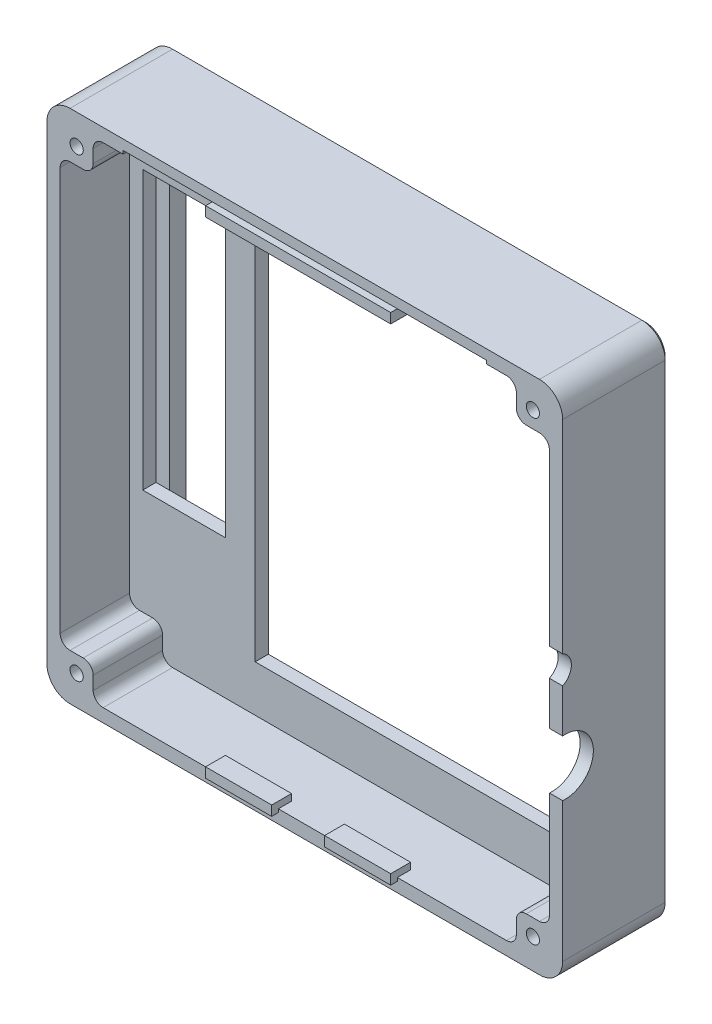
SolidWorks part; units mm, degrees
ref_plane "前视基准面" through (0, 0, 0) normal (0, 0, 1) x (1, 0, 0)
ref_plane "上视基准面" through (0, 0, 0) normal (0, 1, 0) x (1, 0, 0)
ref_plane "右视基准面" through (0, 0, 0) normal (1, 0, 0) x (0, 0, -1)
other "Configuration Table"
sketch "草图1" plane through (0, 0, 0) normal (0, 0, 1) x (1, 0, 0)
  line L1 (-39, -39) -> (39, -39)
  line L2 (-39, -39) -> (-39, 39)
  line L3 (-39, 39) -> (39, 39)
  line L4 (39, -39) -> (39, 39)
  line L5 (-39, -39) -> (39, 39) construction
  line L6 (-39, 39) -> (39, -39) construction
  point P0 (0, 0)
  dimension "D1" = 78
extrude "凸台-拉伸1" add sketch "草图1" along normal blind 5.5
sketch "草图2" plane through (0, 0, 5.5) normal (0, 0, 1) x (1, 0, 0)
  line L1 (-39, -39) -> (39, -39)
  line L2 (-39, -39) -> (-39, 39)
  line L3 (-39, 39) -> (39, 39)
  line L4 (39, -39) -> (39, 39)
  line L5 (-39, -39) -> (39, 39) construction
  line L6 (-39, 39) -> (39, -39) construction
  line L7 (37, 37) -> (-37, 37)
  line L8 (37, 37) -> (37, -37)
  line L9 (37, -37) -> (-37, -37)
  line L10 (-37, 37) -> (-37, -37)
  line L11 (37, 37) -> (-37, -37) construction
  line L12 (37, -37) -> (-37, 37) construction
  line L13 (-37, 37) -> (-32, 37)
  line L14 (-37, 37) -> (-37, 32)
  line L15 (-37, 32) -> (-32, 32)
  line L16 (-32, 37) -> (-32, 32)
  line L17 (37, 37) -> (32, 37)
  line L18 (37, 37) -> (37, 32)
  line L19 (37, 32) -> (32, 32)
  line L20 (32, 37) -> (32, 32)
  line L21 (-37, -37) -> (-32, -37)
  line L22 (-37, -37) -> (-37, -32)
  line L23 (-37, -32) -> (-32, -32)
  line L24 (-32, -37) -> (-32, -32)
  line L25 (37, -37) -> (32, -37)
  line L26 (37, -37) -> (37, -32)
  line L27 (37, -32) -> (32, -32)
  line L28 (32, -37) -> (32, -32)
  point P0 (0, 0)
  point P7 (0, 0)
  line M22 (39, -39) -> (39, 39)
  line M23 (39, 39) -> (-39, 39)
  line M24 (-39, 39) -> (-39, -39)
  line M25 (-39, -39) -> (39, -39)
  dimension "D1" = 2
  dimension "D2" = 5
extrude "凸台-拉伸2" add sketch "草图2" along normal blind 10.5 contours L10 L7 L8 L9 M25 M22 M23 M24 | L16 L7 L10 L15 | L7 L20 L19 L8 | L28 L9 L8 L27 | L9 L24 L23 L10
fillet "圆角1" radius 1.5 12 edges at (37, 32, 10.75) (32, 32, 10.75) (32, 37, 10.75) (37, -32, 10.75) (32, -32, 10.75) (32, -37, 10.75) (-32, -37, 10.75) (-32, -32, 10.75) (-37, -32, 10.75) (-37, 32, 10.75) (-32, 37, 10.75) (-32, 32, 10.75)
fillet "圆角2" radius 3.5 4 edges at (-39, 39, 8) (39, 39, 8) (39, -39, 8) (-39, -39, 8)
sketch "草图3" plane through (0, 0, 0) normal (0, 0, -1) x (-1, 0, 0)
  line L8 (37.5, -35.5) -> (37.5, 35.5)
  line L9 (-35.5, -37.5) -> (35.5, -37.5)
  line L10 (-37.5, 35.5) -> (-37.5, -35.5)
  line L11 (35.5, 37.5) -> (-35.5, 37.5)
  line L12 (37.5, -35.5) -> (37.5, 35.5)
  line L13 (-35.5, -37.5) -> (35.5, -37.5)
  line L14 (-37.5, 35.5) -> (-37.5, -35.5)
  line L15 (35.5, 37.5) -> (-35.5, 37.5)
  arc A8 (37.5, 35.5) -> (35.5, 37.5) centre (35.5, 35.5) ccw
  arc A9 (35.5, -37.5) -> (37.5, -35.5) centre (35.5, -35.5) ccw
  arc A10 (-37.5, -35.5) -> (-35.5, -37.5) centre (-35.5, -35.5) ccw
  arc A11 (-35.5, 37.5) -> (-37.5, 35.5) centre (-35.5, 35.5) ccw
  arc A12 (37.5, 35.5) -> (35.5, 37.5) centre (35.5, 35.5) ccw
  arc A13 (35.5, -37.5) -> (37.5, -35.5) centre (35.5, -35.5) ccw
  arc A14 (-37.5, -35.5) -> (-35.5, -37.5) centre (-35.5, -35.5) ccw
  arc A15 (-35.5, 37.5) -> (-37.5, 35.5) centre (-35.5, 35.5) ccw
  dimension "D1" = 1.5
extrude "切除-拉伸1" cut sketch "草图3" against normal blind 1
sketch "草图4" plane through (0, 0, 1) normal (0, 0, -1) x (-1, 0, 0)
  line L0 (35.5, 37.5) -> (-35.5, 37.5) construction
  line L1 (-32.95, 37.5) -> (32.95, 37.5)
  line L2 (-32.95, 37.5) -> (-32.95, -33)
  line L3 (-32.95, -33) -> (32.95, -33)
  line L4 (32.95, 37.5) -> (32.95, -33)
  line L6 (0, 0) -> (0, 26.6317) construction
  line L7 (-32.95, 36.85) -> (32.95, 36.85)
  line L8 (27.5, 36.85) -> (27.5, 37.5)
  line L9 (-27.5, 36.85) -> (-27.5, 37.5)
  line M10 (35.5, 37.5) -> (-35.5, 37.5)
  dimension "D1" = 70.5
  dimension "D2" = 65.9
  dimension "D3" = 0.65
  dimension "D4" = 55
extrude "切除-拉伸2" cut sketch "草图4" against normal blind 2.5 contours L3 L6 L7 L2 | L6 L3 L4 L7 | L7 L6 L9 M10 | L6 L7 L8 L1
sketch "草图5" plane through (0, 0, 1) normal (0, 0, -1) x (-1, 0, 0)
  line L0 (-35.5, 39) -> (35.5, 39) construction
  line L1 (-34.5, -34.5) -> (34.5, -34.5) construction
  line L2 (-34.5, -34.5) -> (-34.5, 34.5) construction
  line L3 (-34.5, 34.5) -> (34.5, 34.5) construction
  line L4 (34.5, -34.5) -> (34.5, 34.5) construction
  line L5 (-34.5, -34.5) -> (34.5, 34.5) construction
  line L6 (-34.5, 34.5) -> (34.5, -34.5) construction
  circle A0 centre (-34.5, 34.5) radius 1
  circle A1 centre (34.5, 34.5) radius 1
  circle A2 centre (34.5, -34.5) radius 1
  circle A3 centre (-34.5, -34.5) radius 1
  point P0 (0, 0)
  dimension "D2" = 2
  dimension "D1" = 4.5
extrude "切除-拉伸3" cut sketch "草图5" against normal through all
chamfer "倒角1" distance 0.5 angle 45 8 edges at (-39, 0, 0) (-37.9749, -37.9749, 0) (-37.9749, 37.9749, 0) (0, -39, 0) (0, 39, 0) (37.9749, -37.9749, 0) (37.9749, 37.9749, 0) (39, 0, 0)
sketch "草图6" plane through (0, 0, 3.5) normal (0, 0, -1) x (-1, 0, 0)
  line L1 (-27.5, 37.5) -> (27.5, 37.5)
  line L2 (-27.5, 37.5) -> (-27.5, 35.5)
  line L3 (-27.5, 35.5) -> (27.5, 35.5)
  line L4 (27.5, 37.5) -> (27.5, 35.5)
  line L5 (-36, 28) -> (18, 28)
  line L6 (-36, 28) -> (-36, -30)
  line L7 (-36, -30) -> (18, -30)
  line L8 (18, 28) -> (18, -30)
  line L9 (22.5, 26) -> (35, 26)
  line L10 (22.5, 26) -> (22.5, -16)
  line L11 (22.5, -16) -> (35, -16)
  line L12 (35, 26) -> (35, -16)
  dimension "D1" = 2
  dimension "D2" = 54
  dimension "D3" = 30
  dimension "D4" = 58
  dimension "D5" = 36
  dimension "D6" = 22.5
  dimension "D7" = 12.5
  dimension "D8" = 42
  dimension "D9" = 16
extrude "切除-拉伸4" cut sketch "草图6" against normal through all
sketch "草图7" plane through (0, 0, 16) normal (0, 0, 1) x (1, 0, 0)
  line L0 (-15.0283, 0) -> (15.498, 0) construction
  line L17 (0, -8.9343) -> (0, 15.7561) construction
  line L20 (35.5, -37.5) -> (-35.5, -37.5) construction
  line L21 (14, -37.5) -> (4, -37.5)
  line L22 (14, -37.5) -> (14, -36)
  line L23 (14, -36) -> (4, -36)
  line L24 (4, -37.5) -> (4, -36)
  line L25 (-27.5, 37.5) -> (27.5, 37.5) construction
  line L26 (-4, -37.5) -> (-14, -37.5)
  line L27 (-4, -37.5) -> (-4, -36)
  line L28 (-4, -36) -> (-14, -36)
  line L29 (-14, -37.5) -> (-14, -36)
  line L30 (-14, 37.5) -> (14, 37.5)
  line L31 (-14, 37.5) -> (-14, 36)
  line L32 (-14, 36) -> (14, 36)
  line L33 (14, 37.5) -> (14, 36)
  dimension "D1" = 1.5
  dimension "D2" = 28
  dimension "D4" = 1.5
  dimension "D5" = 28
  dimension "D6" = 8
extrude "凸台-拉伸3" add sketch "草图7" along normal blind 1 and the other way blind 2
sketch "草图8" plane through (39, 0, 0) normal (1, 0, 0) x (0, 0, -1)
  line L0 (-16, -35.5) -> (-0.5, -35.5) construction
  line L1 (-16, -35.5) -> (-16, 35.5) construction
  line L2 (-16, 4.8) -> (-16, 0.6) construction
  circle A0 centre (-15.6, -10.2) radius 4.25
  circle A1 centre (-17, 2.7) radius 2.3259
  dimension "D1" = 8.5
  dimension "D4" = 4.2
  dimension "D2" = 25.3
  dimension "D3" = 0.4
  dimension "D5" = 38.2
  dimension "D6" = 1
extrude "切除-拉伸5" cut sketch "草图8" against normal blind 10
